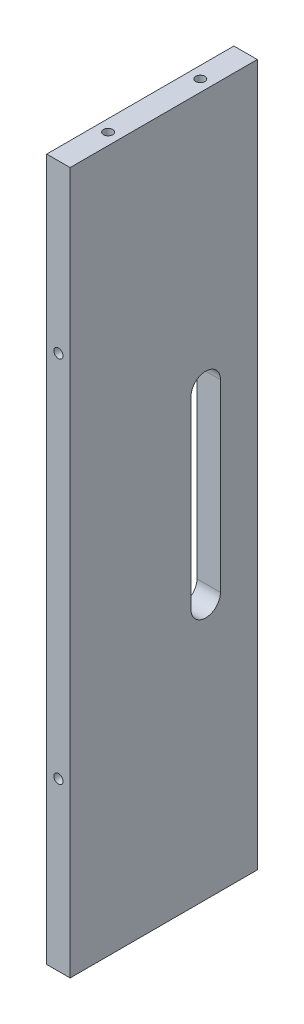
SolidWorks part; units mm, degrees
material "Aleación 6061"
ref_plane "Alzado" through (0, 0, 0) normal (0, 0, 1) x (1, 0, 0)
ref_plane "Planta" through (0, 0, 0) normal (0, 1, 0) x (1, 0, 0)
ref_plane "Vista lateral" through (0, 0, 0) normal (1, 0, 0) x (0, 0, -1)
sketch "Croquis1" plane through (0, 0, 0) normal (1, 0, 0) x (0, 0, -1)
  line L1 (-12.7, -95.25) -> (-63.5, -95.25)
  line L2 (-12.7, -95.25) -> (-12.7, 95.25)
  line L3 (-12.7, 95.25) -> (-63.5, 95.25)
  line L4 (-63.5, -95.25) -> (-63.5, 95.25)
  dimension "D1" = 12.7
  dimension "D2" = 95.25
  dimension "D3" = 63.5
  dimension "D4" = 95.25
  dimension "D5" = 12.7
  dimension "D6" = 95.25
  dimension "D7" = 63.5
  dimension "D8" = 95.25
extrude "Pared_X_1-4in" add sketch "Croquis1" along normal blind 6.35 from offset 139.7
sketch "Croquis2" plane through (0, 0, 0) normal (0, 0, 1) x (1, 0, 0)
  circle A0 centre (-136.525, -50) radius 1.25
  circle A1 centre (-136.525, 50) radius 1.25
  dimension "D1" = 2.5
  dimension "D2" = 2.5
  dimension "D3" = 136.525
  dimension "D4" = 50
  dimension "D5" = 136.525
  dimension "D6" = 50
extrude "Rosca_M3_inferior" cut sketch "Croquis2" along normal blind 10 from offset 12.7
sketch "Croquis3" plane through (0, 0, 0) normal (0, 0, 1) x (1, 0, 0)
  circle A0 centre (-136.525, -50) radius 1.25
  circle A1 centre (-136.525, 50) radius 1.25
  dimension "D1" = 2.5
  dimension "D2" = 2.5
  dimension "D3" = 136.525
  dimension "D4" = 50
  dimension "D5" = 136.525
  dimension "D6" = 50
extrude "Rosca_M3_superior" cut sketch "Croquis3" along normal blind 10 from offset 53.5
sketch "Croquis4" plane through (0, 0, 0) normal (0, 1, 0) x (1, 0, 0)
  circle A0 centre (-136.525, -25) radius 1.25
  circle A1 centre (-136.525, -50) radius 1.25
  dimension "D1" = 2.5
  dimension "D2" = 2.5
  dimension "D3" = 136.525
  dimension "D4" = 25
  dimension "D5" = 136.525
  dimension "D6" = 50
extrude "Rosca_M3_esquina_+Y" cut sketch "Croquis4" along normal blind 10 from offset 85.25
sketch "Croquis5" plane through (0, 0, 0) normal (0, 1, 0) x (1, 0, 0)
  circle A0 centre (-136.525, -25) radius 1.25
  circle A1 centre (-136.525, -50) radius 1.25
  dimension "D1" = 2.5
  dimension "D2" = 2.5
  dimension "D3" = 136.525
  dimension "D4" = 25
  dimension "D5" = 136.525
  dimension "D6" = 50
extrude "Rosca_M3_esquina_-Y" cut sketch "Croquis5" along normal blind 10 from offset 95.25
sketch "Croquis6" plane through (0, 0, 0) normal (1, 0, 0) x (0, 0, -1)
  line L0 (-30.7, -25) -> (-30.7, 25)
  line L1 (-22.7, 25) -> (-22.7, -25)
  arc A0 (-30.7, 25) -> (-22.7, 25) centre (-26.7, 25) cw
  arc A1 (-22.7, -25) -> (-30.7, -25) centre (-26.7, -25) cw
  dimension "D1" = 4
  dimension "D2" = 4
  dimension "D3" = 30.7
  dimension "D4" = 25
  dimension "D5" = 30.7
  dimension "D6" = 25
  dimension "D7" = 22.7
  dimension "D8" = 25
  dimension "D9" = 22.7
  dimension "D10" = 25
extrude "Paso_cable_alimentacion" cut sketch "Croquis6" along normal blind 6.35 from offset 139.7
